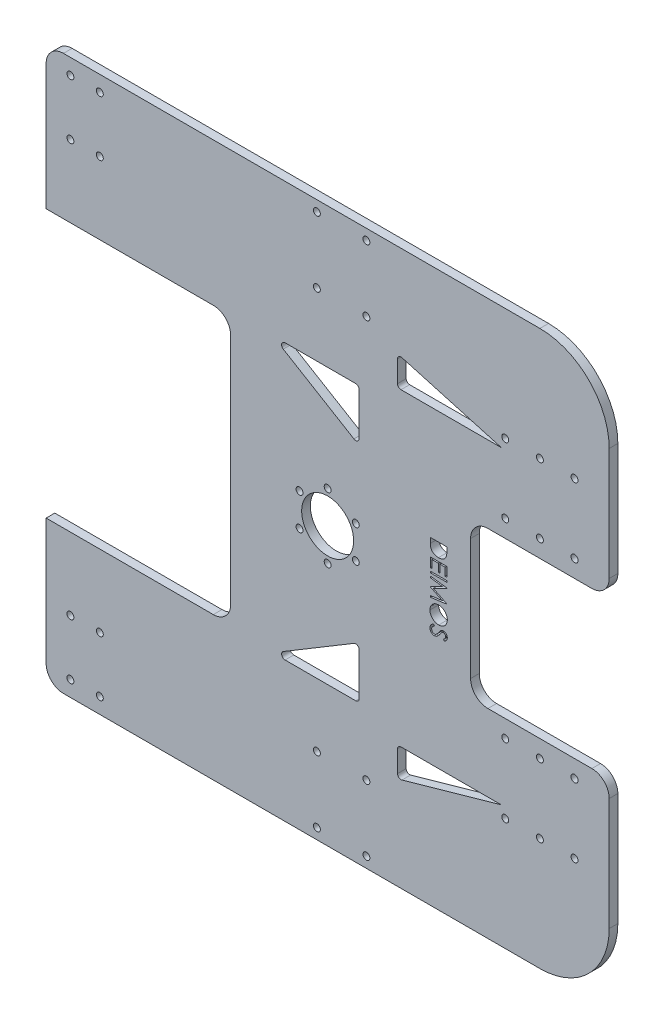
SolidWorks part; units mm, degrees
other "Markup1"
sketch "Sketch11" plane through (-21.3462, -140, 0) normal (-0.3162, -0.6649, -0.6767) x (-0.9458, 0.2765, 0.1703)
material "6061-T6 (SS)"
ref_plane "Front Plane" through (0, 0, 0) normal (0, 0, 1) x (1, 0, 0)
ref_plane "Top Plane" through (0, 0, 0) normal (0, 1, 0) x (1, 0, 0)
ref_plane "Right Plane" through (0, 0, 0) normal (1, 0, 0) x (0, 0, -1)
sketch "Sketch1" plane through (0, 0, 0) normal (0, 0, 1) x (1, 0, 0)
  line L53 (-21.3462, 160) -> (303.6538, 160)
  line L54 (-21.3462, 160) -> (-21.3462, 60)
  line L56 (-21.3462, 110) -> (303.6538, 110) construction
  line L57 (-21.3462, 60) -> (303.6538, 60)
  line L70 (141.1538, 0) -> (303.6538, 0) construction
  line L72 (303.6538, 160) -> (303.6538, 60)
  line L108 (-21.3462, 160) -> (303.6538, 160)
  line L109 (-21.3462, 60) -> (303.6538, 60)
  line L110 (-21.3462, -110) -> (303.6538, -110) construction
  line L111 (-21.3462, -60) -> (303.6538, -60)
  line L112 (-21.3462, -160) -> (303.6538, -160)
  line L124 (303.6538, -160) -> (303.6538, -60)
  line L129 (-21.3462, -60) -> (303.6538, -60)
  line L131 (-21.3462, -160) -> (-21.3462, -60)
  line L132 (-21.3462, -160) -> (303.6538, -160)
  line L133 (-21.3462, 60) -> (303.6538, 60)
  line L134 (-21.3462, 60) -> (-21.3462, -60)
  line L135 (303.6538, 60) -> (303.6538, -60)
  line L136 (-21.3462, -60) -> (303.6538, -60)
  line L139 (233.6538, -60) -> (283.6538, -60) construction
  line L140 (233.6538, -60) -> (233.6538, -50) construction
  line L141 (283.6538, -60) -> (283.6538, -50) construction
  line L142 (233.6538, -50) -> (283.6538, -50) construction
  line L143 (233.6538, 60) -> (283.6538, 60) construction
  line L144 (233.6538, 60) -> (233.6538, 50) construction
  line L145 (283.6538, 60) -> (283.6538, 50) construction
  line L146 (233.6538, 50) -> (283.6538, 50) construction
  circle A0 centre (141.1538, 0) radius 15
  circle A1 centre (141.1538, 0) radius 18.75 construction
  circle A2 centre (141.1538, 18.75) radius 2
  circle A12 centre (157.3918, 9.375) radius 2
  circle A13 centre (157.3918, -9.375) radius 2
  circle A14 centre (141.1538, -18.75) radius 2
  circle A15 centre (124.9159, -9.375) radius 2
  circle A16 centre (124.9159, 9.375) radius 2
  point P35 (141.1538, 0)
  point P42 (141.1538, -60)
  point P44 (-21.3462, 0)
  dimension "D7" = 320
  dimension "D2" = 20
  dimension "D8" = 120
  dimension "D10" = 10
  dimension "D5" = 4
  dimension "D6" = 6
  dimension "D3" = 30
  dimension "D4" = 37.5
  dimension "D13" = 325
  dimension "D9" = 50
  dimension "D14" = 20
extrude "Boss-Extrude1" add sketch "Sketch1" along normal blind 5
fillet "Fillet1" radius 10 2 edges at (-21.3462, -160, 2.5) (-21.3462, 160, 2.5)
fillet "Fillet2" radius 40 2 edges at (303.6538, -160, 2.5) (303.6538, 160, 2.5)
sketch "Sketch4" plane through (0, 0, 0) normal (0, 0, 1) x (1, 0, 0)
  line L0 (303.6538, 45) -> (223.6538, 45)
  line L1 (303.6538, 120) -> (303.6538, -120) construction
  line L2 (223.6538, 45) -> (223.6538, -45)
  line L3 (223.6538, -45) -> (303.6538, -45)
  line L4 (303.6538, 45) -> (303.6538, -45)
  line L5 (109.345, -79.2857) -> (159.345, -49.2857)
  line L6 (159.345, -49.2857) -> (159.345, -79.2857)
  line L7 (159.345, -79.2857) -> (109.345, -79.2857)
  line L8 (181.4699, -89.2857) -> (241.4699, -89.2857)
  line L9 (241.4699, -89.2857) -> (181.4699, -106.2857)
  line L10 (181.4699, -106.2857) -> (181.4699, -89.2857)
  line L11 (-21.3462, 0) -> (303.6538, 0) construction
  line L13 (-21.3462, 150) -> (-21.3462, -150) construction
  line L14 (159.345, 49.2857) -> (159.345, 79.2857)
  line L15 (159.345, 79.2857) -> (109.345, 79.2857)
  line L16 (109.345, 79.2857) -> (159.345, 49.2857)
  line L17 (241.4699, 89.2857) -> (181.4699, 106.2857)
  line L18 (181.4699, 106.2857) -> (181.4699, 89.2857)
  line L19 (181.4699, 89.2857) -> (241.4699, 89.2857)
  point P4 (303.6538, 0)
  dimension "D1" = 45
  dimension "D2" = 90
  dimension "D3" = 80
  dimension "D4" = 10
  dimension "D5" = 30
  dimension "D6" = 17
  dimension "D7" = 50
  dimension "D8" = 60
extrude "Cut-Extrude5" cut sketch "Sketch4" along normal blind 10 contours L4 L3 L2 L0 | L10 L8 L9 | L7 L5 L6 | L14 L15 L16 | L17 L18 L19
fillet "Fillet4" radius 10 4 edges at (303.6538, 45, 2.5) (223.6538, 45, 2.5) (223.6538, -45, 2.5) (303.6538, -45, 2.5)
fillet "Fillet5" radius 2 10 edges at (159.345, 49.2857, 2.5) (109.345, 79.2857, 2.5) (159.345, 79.2857, 2.5) (181.4699, 89.2857, 2.5) (181.4699, 106.2857, 2.5) (181.4699, -106.2857, 2.5) (181.4699, -89.2857, 2.5) (159.345, -79.2857, 2.5) (159.345, -49.2857, 2.5) (109.345, -79.2857, 2.5)
sketch "Sketch6" plane through (0, 0, 5) normal (0, 0, 1) x (1, 0, 0)
  line L0 (200.4405, 160) -> (200.4405, -160) construction
  line L1 (-11.3462, 160) -> (263.6538, 160) construction
  line L2 (-11.3462, -160) -> (263.6538, -160) construction
sketch "Sketch8" plane through (0, 0, 5) normal (0, 0, 1) x (1, 0, 0)
  text T0 "DEIMOS" font "Century Gothic" height in points 36
extrude "Cut-Extrude7" cut sketch "Sketch8" against normal blind 34
sketch "Sketch9" plane through (0, 0, 5) normal (0, 0, 1) x (1, 0, 0)
  line L0 (-11.3462, -160) -> (263.6538, -160) construction
  line L4 (-21.3462, 0) -> (223.6538, 0) construction
  line L5 (-21.3462, 150) -> (-21.3462, -150) construction
  line L6 (223.6538, 35) -> (223.6538, -35) construction
  line L7 (-7.3462, 119) -> (9.6338, 151) construction
  line L8 (-7.3462, -151) -> (9.6338, -151) construction
  line L9 (-7.3462, -151) -> (-7.3462, -119) construction
  line L10 (-7.3462, -119) -> (9.6338, -119) construction
  line L11 (9.6338, -151) -> (9.6338, -119) construction
  line L12 (-7.3462, -151) -> (9.6338, -119) construction
  line L13 (-7.3462, -119) -> (9.6338, -151) construction
  line L14 (-7.3462, 151) -> (9.6338, 119) construction
  line L15 (9.6338, 151) -> (9.6338, 119) construction
  line L16 (-7.3462, 119) -> (9.6338, 119) construction
  line L17 (-7.3462, 151) -> (-7.3462, 119) construction
  line L18 (-7.3462, 151) -> (9.6338, 151) construction
  circle A2 centre (-7.3462, -119) radius 2
  circle A3 centre (9.6338, -119) radius 2
  circle A4 centre (-7.3462, -151) radius 2
  circle A5 centre (9.6338, -151) radius 2
  circle A6 centre (9.6338, 151) radius 2
  circle A7 centre (-7.3462, 151) radius 2
  circle A8 centre (9.6338, 119) radius 2
  circle A9 centre (-7.3462, 119) radius 2
  point P15 (1.1438, -135)
  point P32 (1.1438, 135)
  dimension "D2" = 16.98
  dimension "D4" = 4
  dimension "D1" = 25
  dimension "D3" = 14
extrude "Cut-Extrude8" cut sketch "Sketch9" against normal blind 10
sketch "Sketch10" plane through (0, 0, 5) normal (0, 0, 1) x (1, 0, 0)
  line L0 (-21.3462, 150) -> (-21.3462, -150) construction
  line L1 (-21.3462, 77.2978) -> (85.1568, 77.2978)
  line L2 (-21.3462, 77.2978) -> (-21.3462, -77.2978)
  line L3 (-21.3462, -77.2978) -> (85.1568, -77.2978)
  line L4 (85.1568, 77.2978) -> (85.1568, -77.2978)
  point P6 (-21.3462, 0)
extrude "Cut-Extrude9" cut sketch "Sketch10" against normal blind 10
fillet "Fillet6" radius 10 2 edges at (85.1568, -77.2978, 2.5) (85.1568, 77.2978, 2.5)
sketch "Sketch14" plane through (0, 0, 5) normal (0, 0, 1) x (1, 0, 0)
  line L0 (0, 0) -> (316.9435, 0) construction
  circle A1 centre (134.9181, 115.8743) radius 2
  circle A2 centre (134.9181, 115.8743) radius 2
  circle A3 centre (163.5267, 115.8743) radius 2
  circle A4 centre (163.5267, 115.8743) radius 2
  circle A5 centre (134.9181, 153.8743) radius 2
  circle A6 centre (134.9181, 153.8743) radius 2
  circle A7 centre (163.5267, 153.8743) radius 2
  circle A8 centre (163.5267, 153.8743) radius 2
  circle A32 centre (163.5267, -153.8743) radius 2
  circle A33 centre (134.9181, -153.8743) radius 2
  circle A34 centre (163.5267, -115.8743) radius 2
  circle A35 centre (134.9181, -115.8743) radius 2
  dimension "D1" = 0
  dimension "D2" = 0
  dimension "D3" = 0
  dimension "D4" = 0
sketch "Sketch15" plane through (0, 0, 5) normal (0, 0, 1) x (1, 0, 0)
  line L0 (83.1511, 0) -> (316.9435, 0) construction
  line L1 (0, 0) -> (316.9435, 0) construction
  circle A1 centre (243.6538, -55) radius 2
  circle A2 centre (243.6538, -55) radius 2
  circle A3 centre (283.6538, -55) radius 2.0723
  circle A4 centre (283.6538, -55) radius 2.0723
  circle A5 centre (283.6538, -95) radius 2
  circle A6 centre (283.6538, -95) radius 2
  circle A7 centre (263.6538, -95) radius 2
  circle A8 centre (263.6538, -95) radius 2
  circle A9 centre (243.6538, -95) radius 2
  circle A10 centre (243.6538, -95) radius 2
  circle A15 centre (263.6538, -55) radius 2
  circle A16 centre (263.6538, 55) radius 2
  circle A17 centre (243.6538, 95) radius 2
  circle A18 centre (263.6538, 95) radius 2
  circle A19 centre (283.6538, 95) radius 2
  circle A20 centre (283.6538, 55) radius 2.0723
  circle A21 centre (243.6538, 55) radius 2
  dimension "D6" = 4
  dimension "D1" = 0
  dimension "D2" = 0
  dimension "D3" = 0
  dimension "D4" = 0
  dimension "D5" = 0
extrude "Cut-Extrude10" cut sketch "Sketch14" against normal through all
extrude "Cut-Extrude11" cut sketch "Sketch15" against normal through all
